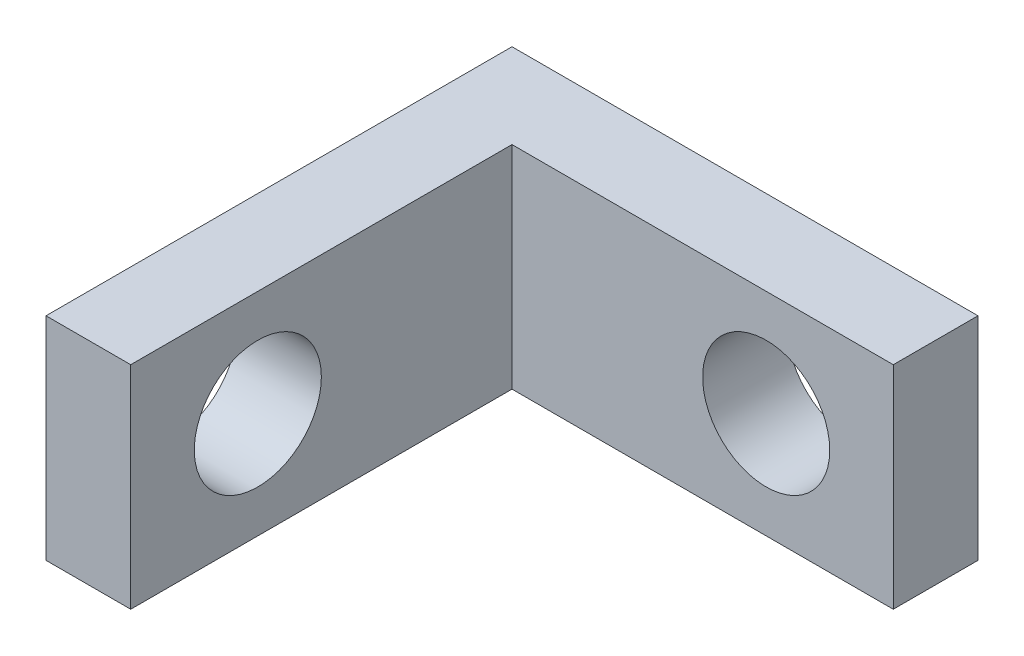
SolidWorks part; units mm, degrees
ref_plane "前视基准面" through (0, 0, 0) normal (0, 0, 1) x (1, 0, 0)
ref_plane "上视基准面" through (0, 0, 0) normal (0, 1, 0) x (1, 0, 0)
ref_plane "右视基准面" through (0, 0, 0) normal (1, 0, 0) x (0, 0, -1)
sketch "草图1" plane through (0, 0, 0) normal (1, 0, 0) x (0, 0, -1)
  line L0 (0, 0) -> (-8, 0) construction
  line L1 (-8, 0) -> (-11, 0) construction
  line L2 (-11, 0) -> (-11, 2.5)
  line L3 (-11, 2.5) -> (0, 2.5)
  line L4 (0, 2.5) -> (0, 0)
  line L5 (0, 0) -> (0, -2.5)
  line L6 (0, -2.5) -> (-11, -2.5)
  line L7 (-11, -2.5) -> (-11, 0)
  circle A0 centre (-8, 0) radius 1.5
  dimension "D2" = 3
  dimension "D1" = 8
  dimension "D3" = 2.5
  dimension "D4" = 2.5
extrude "凸台-拉伸1" add sketch "草图1" along normal blind 2
sketch "草图2" plane through (2, 0, 0) normal (1, 0, 0) x (0, 0, -1)
  line L0 (-11, -2.5) -> (0, -2.5) construction
  line L1 (0, 2.5) -> (-2, 2.5)
  line L2 (0, 2.5) -> (0, -2.5)
  line L3 (0, -2.5) -> (-2, -2.5)
  line L4 (-2, 2.5) -> (-2, -2.5)
  dimension "D1" = 2
extrude "凸台-拉伸2" add sketch "草图2" along normal blind 9
sketch "草图3" plane through (0, 0, 2) normal (0, 0, 1) x (1, 0, 0)
  line L0 (11, 0) -> (8, 0) construction
  line L1 (11, 2.5) -> (11, -2.5) construction
  circle A0 centre (8, 0) radius 1.5
  dimension "D1" = 3
extrude "切除-拉伸1" cut sketch "草图3" against normal blind 6
